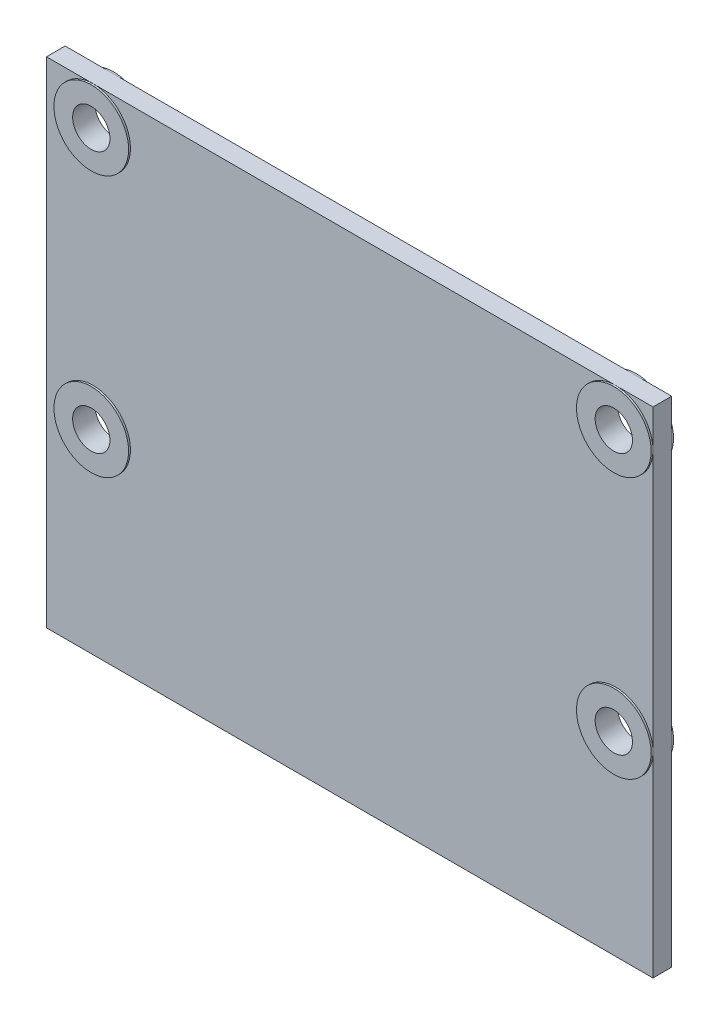
SolidWorks part; units mm, degrees
ref_plane "Front Plane" through (0, 0, 0) normal (0, 0, 1) x (1, 0, 0)
ref_plane "Top Plane" through (0, 0, 0) normal (0, 1, 0) x (1, 0, 0)
ref_plane "Right Plane" through (0, 0, 0) normal (1, 0, 0) x (0, 0, -1)
sketch "Sketch1" plane through (0, 0, 0) normal (0, 0, 1) x (1, 0, 0)
  line L1 (-16.25, 13.25) -> (16.25, 13.25)
  line L2 (-16.25, 13.25) -> (-16.25, -13.25)
  line L3 (-16.25, -13.25) -> (16.25, -13.25)
  line L4 (16.25, 13.25) -> (16.25, -13.25)
  line L5 (-16.25, 13.25) -> (16.25, -13.25) construction
  line L6 (-16.25, -13.25) -> (16.25, 13.25) construction
  point P0 (0, 0)
  dimension "D1" = 32.5
  dimension "D2" = 26.5
extrude "Boss-Extrude1" add sketch "Sketch1" along normal blind 1
sketch "Sketch2" plane through (0, 0, 1) normal (0, 0, 1) x (1, 0, 0)
  line L0 (16.25, 13.25) -> (-16.25, 13.25) construction
  line L1 (16.25, -13.25) -> (16.25, 13.25) construction
  circle A0 centre (-13.75, 11.25) radius 1
  circle A1 centre (14.25, 11.25) radius 1
  circle A2 centre (14.25, -2.75) radius 1
  circle A3 centre (-13.75, -2.75) radius 1
  circle A4 centre (-10, 4.25) radius 0.75
  circle A5 centre (10, 4.25) radius 0.75
  point P16 (0, 0)
  point P18 (0, 0)
  dimension "D9" = 2
  dimension "D10" = 2
  dimension "D11" = 2
  dimension "D12" = 2
  dimension "D13" = 1.5
  dimension "D14" = 1.5
  dimension "D1" = 28
  dimension "D3" = 14
  dimension "D4" = 14
  dimension "D5" = 2
  dimension "D6" = 2
  dimension "D7" = 2
  dimension "D8" = 2
  dimension "D15" = 20
  dimension "D16" = 10
  dimension "D17" = 9
extrude "Cut-Extrude1" cut sketch "Sketch2" against normal blind 2 contours A0 | A3 | A2 | A1
sketch "Sketch3" plane through (0, 0, 1) normal (0, 0, 1) x (1, 0, 0)
  circle A0 centre (-13.75, 11.25) radius 2
  circle A1 centre (14.25, 11.25) radius 2
  circle A2 centre (14.25, -2.75) radius 2
  circle A3 centre (-13.75, -2.75) radius 2
  circle A4 centre (-13.75, 11.25) radius 1
  circle A5 centre (14.25, 11.25) radius 1
  circle A6 centre (14.25, -2.75) radius 1
  circle A7 centre (-13.75, -2.75) radius 1
  circle A8 centre (-13.75, 11.25) radius 1
  circle A9 centre (14.25, 11.25) radius 1
  circle A10 centre (14.25, -2.75) radius 1
  circle A11 centre (-13.75, -2.75) radius 1
  circle M3 centre (14.25, 11.25) radius 1
  circle M4 centre (14.25, -2.75) radius 1
  circle M5 centre (-13.75, -2.75) radius 1
  circle M8 centre (-13.75, 11.25) radius 1
  dimension "D1" = 4
  dimension "D2" = 4
  dimension "D3" = 4
  dimension "D4" = 4
  dimension "D5" = 1
extrude "Boss-Extrude3" add sketch "Sketch3" along normal blind 0.1 and the other way blind 1.1 contours A0 M8 | A1 M3 | A2 M4 | A3 M5
